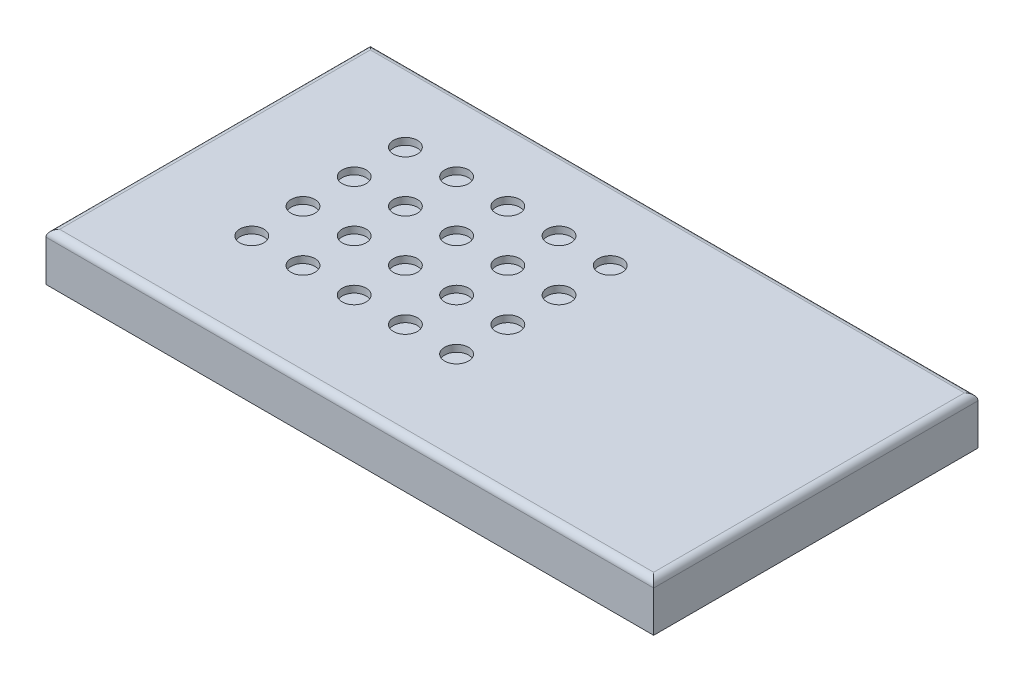
SolidWorks part; units mm, degrees
material "1.7319 (20MoCrS3)"
ref_plane "Plan de face" through (0, 0, 0) normal (0, 0, 1) x (1, 0, 0)
ref_plane "Plan de dessus" through (0, 0, 0) normal (0, 1, 0) x (1, 0, 0)
ref_plane "Plan de droite" through (0, 0, 0) normal (1, 0, 0) x (0, 0, -1)
sketch "Esquisse1" plane through (0, 0, 0) normal (0, 1, 0) x (1, 0, 0)
  line L1 (0, 0) -> (35.6, 0)
  line L2 (0, 0) -> (0, 19)
  line L3 (0, 19) -> (35.6, 19)
  line L4 (35.6, 0) -> (35.6, 19)
  dimension "D1" = 35.6
  dimension "D2" = 19
extrude "Boss.-Extru.1" add sketch "Esquisse1" along normal blind 2.8
fillet "Congé1" radius 0.4 4 edges at (0, 2.8, -9.5) (17.8, 2.8, -19) (35.6, 2.8, -9.5) (17.8, 2.8, 0)
sketch "Esquisse2" plane through (0, 2.8, 0) normal (0, 1, 0) x (1, 0, 0)
  circle A0 centre (6.3615, 14.6932) radius 0.7019
extrude "Enlèv. mat.-Extru.1" cut sketch "Esquisse2" against normal blind 0.4
sketch "Esquisse3" plane through (0, 2.8, 0) normal (0, 1, 0) x (1, 0, 0)
  line L0 (6.3615, 14.6932) -> (25.8839, 14.6932)
  line L1 (6.3615, 14.6932) -> (6.3615, 5.8027)
pattern_linear "Répétition linéaire1" count 5 spacing 3 along (1, 0, 0) count 4 spacing 3 along (0, 0, 1) of "Enlèv. mat.-Extru.1"
